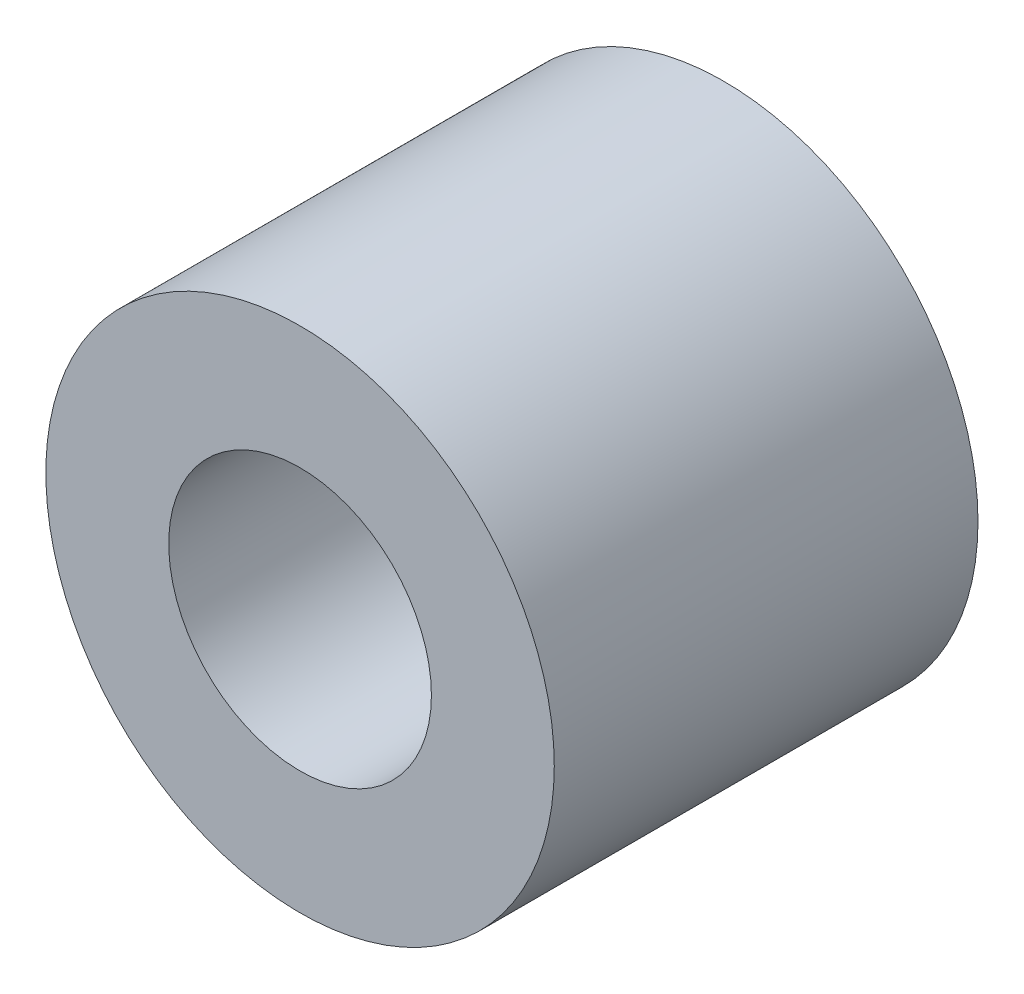
SolidWorks part; units mm, degrees
ref_plane "Plan de face" through (0, 0, 0) normal (0, 0, 1) x (1, 0, 0)
ref_plane "Plan de dessus" through (0, 0, 0) normal (0, 1, 0) x (1, 0, 0)
ref_plane "Plan de droite" through (0, 0, 0) normal (1, 0, 0) x (0, 0, -1)
sketch "Esquisse1" plane through (0, 0, 0) normal (0, 0, 1) x (1, 0, 0)
  circle A0 centre (0, 0.4078) radius 3
  circle A1 centre (0, 0.4078) radius 1.55
  dimension "D1" = 3.1
  dimension "D2" = 6
extrude "Boss.-Extru.1" add sketch "Esquisse1" along normal blind 5
sketch "Esquisse2" plane through (0, 0, 5) normal (0, 0, 1) x (1, 0, 0)
  line L0 (0, 0) -> (0, 50000) construction
  arc A3 (-1.1912, -2.8371) -> (1.1912, -2.8371) centre (0, -5.6119) cw
  arc A6 (-1.1912, -3.0457) -> (1.1912, -3.0457) centre (0, -5.8205) cw
  circle A7 centre (0, 0.4078) radius 3 construction
  point P9 (0.9759, -3.3385)
  point P10 (1.4343, -3.9907)
  point P11 (0, 0)
  point P12 (0, 0)
  point P13 (0, 0)
  point P14 (-1.0548, -3.7562)
  point P17 (-1.1912, -3.0457)
